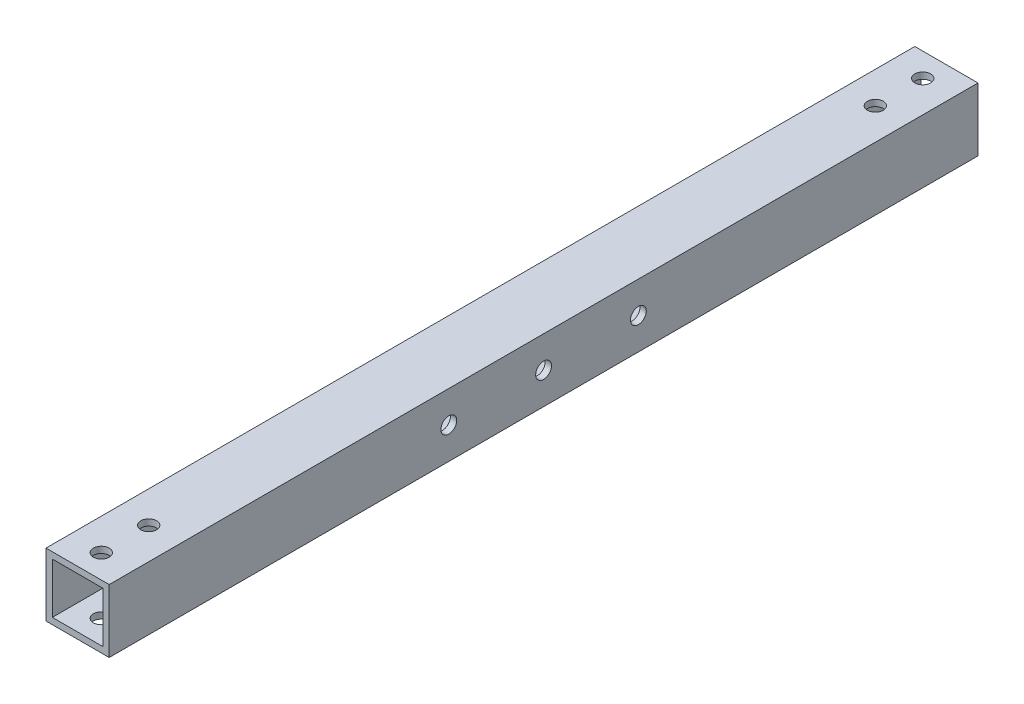
SolidWorks part; units mm, degrees
material "6063-T5"
ref_plane "前视基准面" through (0, 0, 0) normal (0, 0, 1) x (1, 0, 0)
ref_plane "上视基准面" through (0, 0, 0) normal (0, 1, 0) x (1, 0, 0)
ref_plane "右视基准面" through (0, 0, 0) normal (1, 0, 0) x (0, 0, -1)
sketch "草图1" plane through (0, 0, 0) normal (0, 0, 1) x (1, 0, 0)
  line L1 (-10, 10) -> (10, 10)
  line L2 (-10, 10) -> (-10, -10)
  line L3 (-10, -10) -> (10, -10)
  line L4 (10, 10) -> (10, -10)
  line L5 (-10, 10) -> (10, -10) construction
  line L6 (-10, -10) -> (10, 10) construction
  line L7 (-8, 8) -> (8, 8)
  line L8 (-8, 8) -> (-8, -8)
  line L9 (-8, -8) -> (8, -8)
  line L10 (8, 8) -> (8, -8)
  line L11 (-8, 8) -> (8, -8) construction
  line L12 (-8, -8) -> (8, 8) construction
  point P0 (0, 0)
  point P5 (0, 0)
  point P11 (8, 0)
  dimension "D1" = 20
  dimension "D2" = 20
  dimension "D3" = 2
  dimension "D4" = 2
extrude "凸台-拉伸1" add sketch "草图1" along normal blind 275
sketch "草图3" plane through (0, -10, 0) normal (0, -1, 0) x (1, 0, 0)
  line L0 (-52.7276, 137.5) -> (77.3648, 137.5) construction
  line L1 (-10, 275) -> (10, 275) construction
  line L2 (-10, 0) -> (10, 0) construction
  line L3 (0, 41.9014) -> (0, -37.6366) construction
  line L5 (0, 30) -> (0, 0) construction
  line L6 (0, 15) -> (26.5688, 15) construction
  circle A0 centre (0, 7.5) radius 2.5
  circle A1 centre (0, 267.5) radius 2.5
  circle A2 centre (0, 22.5) radius 2.5
  circle A3 centre (0, 252.5) radius 2.5
  dimension "D1" = 5
  dimension "D2" = 15
  dimension "D5" = 30
extrude "切除-拉伸2" cut sketch "草图3" against normal through all
sketch "草图4" plane through (-10, 0, 0) normal (-1, 0, 0) x (0, 0, 1)
  line L0 (137.5, 28.5228) -> (137.5, -37.6675) construction
  line L1 (0, 10) -> (0, -10) construction
  line L2 (275, 10) -> (275, -10) construction
  line L3 (107.5, 0) -> (137.5, 0) construction
  circle A0 centre (107.5, 0) radius 2.5
  circle A1 centre (167.5, 0) radius 2.5
  circle A2 centre (137.5, 0) radius 2.5
  dimension "D2" = 5
  dimension "D1" = 5
  dimension "D3" = 30
extrude "切除-拉伸3" cut sketch "草图4" against normal through all
